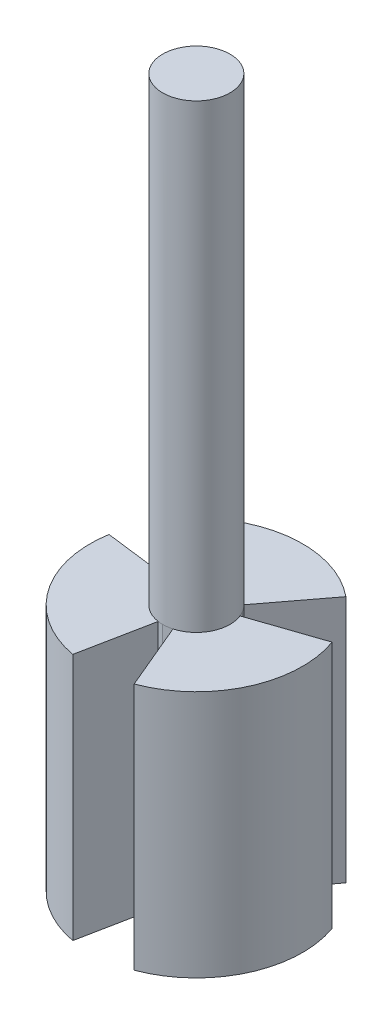
SolidWorks part; units mm, degrees
ref_plane "Front Plane" through (0, 0, 0) normal (0, 0, 1) x (1, 0, 0)
ref_plane "Top Plane" through (0, 0, 0) normal (0, 1, 0) x (1, 0, 0)
ref_plane "Right Plane" through (0, 0, 0) normal (1, 0, 0) x (0, 0, -1)
sketch "Sketch1" plane through (0, 0, 0) normal (0, 1, 0) x (1, 0, 0)
  circle A0 centre (0, 0) radius 9.5
  dimension "D1" = 19
extrude "Boss-Extrude1" add sketch "Sketch1" along normal blind 200
sketch "Sketch2" plane through (0, 0, 0) normal (0, -1, 0) x (1, 0, 0)
  circle A0 centre (0, 0) radius 30
  circle A1 centre (0, 0) radius 9.5 construction
  circle A2 centre (0, 0) radius 9.5
  dimension "D1" = 60
extrude "Boss-Extrude2" add sketch "Sketch2" against normal blind 70
sketch "Sketch3" plane through (0, 70, 0) normal (0, 1, 0) x (1, 0, 0)
  line L0 (-5.9215, -32.2581) -> (-1.3829, -9.3988)
  line L1 (-1.3829, -9.3988) -> (0, -9.5)
  line L2 (0, -9.5) -> (2.5539, -9.1503)
  line L3 (2.5539, -9.1503) -> (12.2863, -32.2581)
  line L4 (-5.9215, -32.2581) -> (12.2863, -32.2581)
  circle A1 centre (0, 0) radius 9.5 construction
  circle A2 centre (0, 0) radius 9.5 construction
extrude "Cut-Extrude1" cut sketch "Sketch3" against normal through all
pattern_circular "CirPattern1" count 3 over 360 about axis through (0, 0, 0) along (0, 1, 0) of "Cut-Extrude1"
